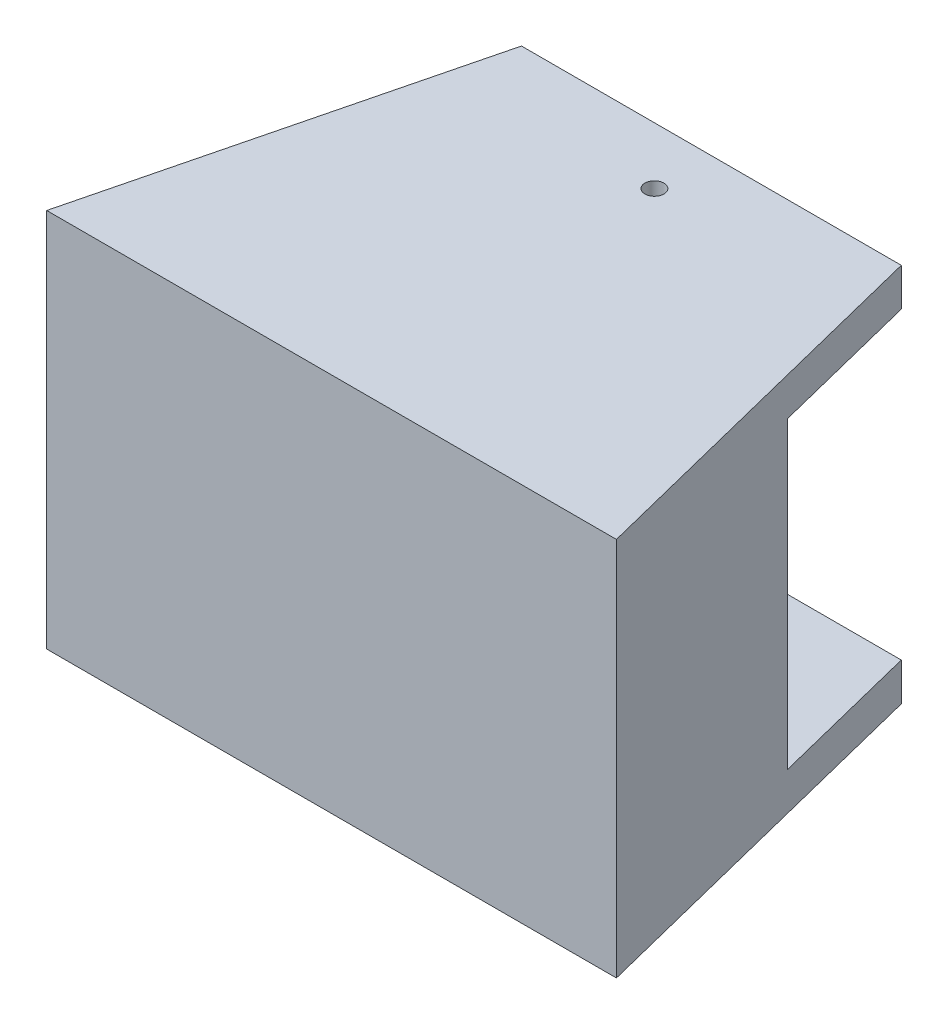
SolidWorks part; units mm, degrees
ref_plane "前视基准面" through (0, 0, 0) normal (0, 0, 1) x (1, 0, 0)
ref_plane "上视基准面" through (0, 0, 0) normal (0, 1, 0) x (1, 0, 0)
ref_plane "右视基准面" through (0, 0, 0) normal (1, 0, 0) x (0, 0, -1)
sketch "草图1" plane through (0, 0, 0) normal (0, 1, 0) x (1, 0, 0)
  line L0 (-50, 100) -> (50, 100)
  line L3 (-100, -100) -> (100, -100)
  line L5 (-100, 100) -> (100, -100) construction
  line L6 (-100, -100) -> (100, 100) construction
  line L7 (50, 100) -> (100, -100)
  line L8 (0, 100) -> (0, -100) construction
  line L9 (-50, 100) -> (-100, -100)
  point P0 (0, 0)
extrude "凸台-拉伸1" add sketch "草图1" along normal blind 100
sketch "草图2" plane through (0, 0, 0) normal (1, 0, 0) x (0, 0, -1)
  line L0 (100, 10) -> (100, 90)
  line L1 (100, 100) -> (100, 0) construction
  line L3 (100, 90) -> (60, 90)
  line L4 (60, 90) -> (60, 10)
  line L5 (100, 10) -> (60, 10)
  point P9 (60, 50)
extrude "切除-拉伸2" cut sketch "草图2" against normal through all both and the other way through all
sketch "草图3" plane through (0, 100, 0) normal (0, 1, 0) x (1, 0, 0)
  circle A0 centre (0, 85) radius 2.5
extrude "切除-拉伸3" cut sketch "草图3" against normal through all both and the other way through all
sketch "草图4" plane through (0, 100, 0) normal (0, 1, 0) x (1, 0, 0)
  line L0 (-75, 0) -> (75, 0)
  line L1 (-50, 100) -> (-100, -100) construction
  line L2 (100, -100) -> (50, 100) construction
  line L3 (75, 0) -> (100, -100)
  line L4 (100, -100) -> (-100, -100)
  line L5 (-100, -100) -> (-75, 0)
extrude "切除-拉伸4" cut sketch "草图4" against normal through all
